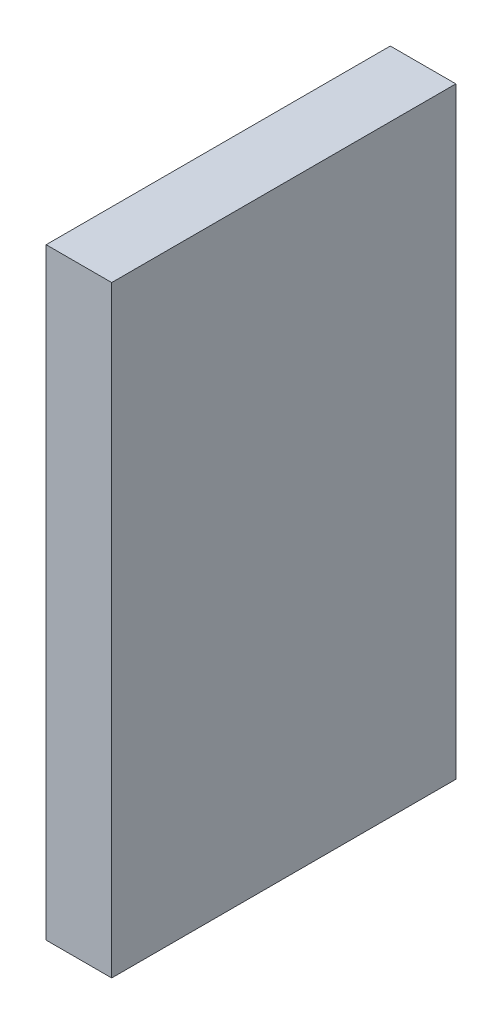
SolidWorks part; units mm, degrees
ref_plane "Front Plane" through (0, 0, 0) normal (0, 0, 1) x (1, 0, 0)
ref_plane "Top Plane" through (0, 0, 0) normal (0, 1, 0) x (1, 0, 0)
ref_plane "Right Plane" through (0, 0, 0) normal (1, 0, 0) x (0, 0, -1)
sketch "Sketch1" plane through (0, 0, 0) normal (0, 0, 1) x (1, 0, 0)
  line L2 (215, -300) -> (234.05, -300)
  line L3 (234.05, -300) -> (-234.05, -300) construction
  line L4 (234.05, -300) -> (234.05, -125)
  line L6 (215, -300) -> (215, -125) construction
  line L7 (215, -300) -> (215, -125)
  line L8 (215, -125) -> (234.05, -125)
extrude "Boss-Extrude1" add sketch "Sketch1" along normal up to surface (100 mm away)
